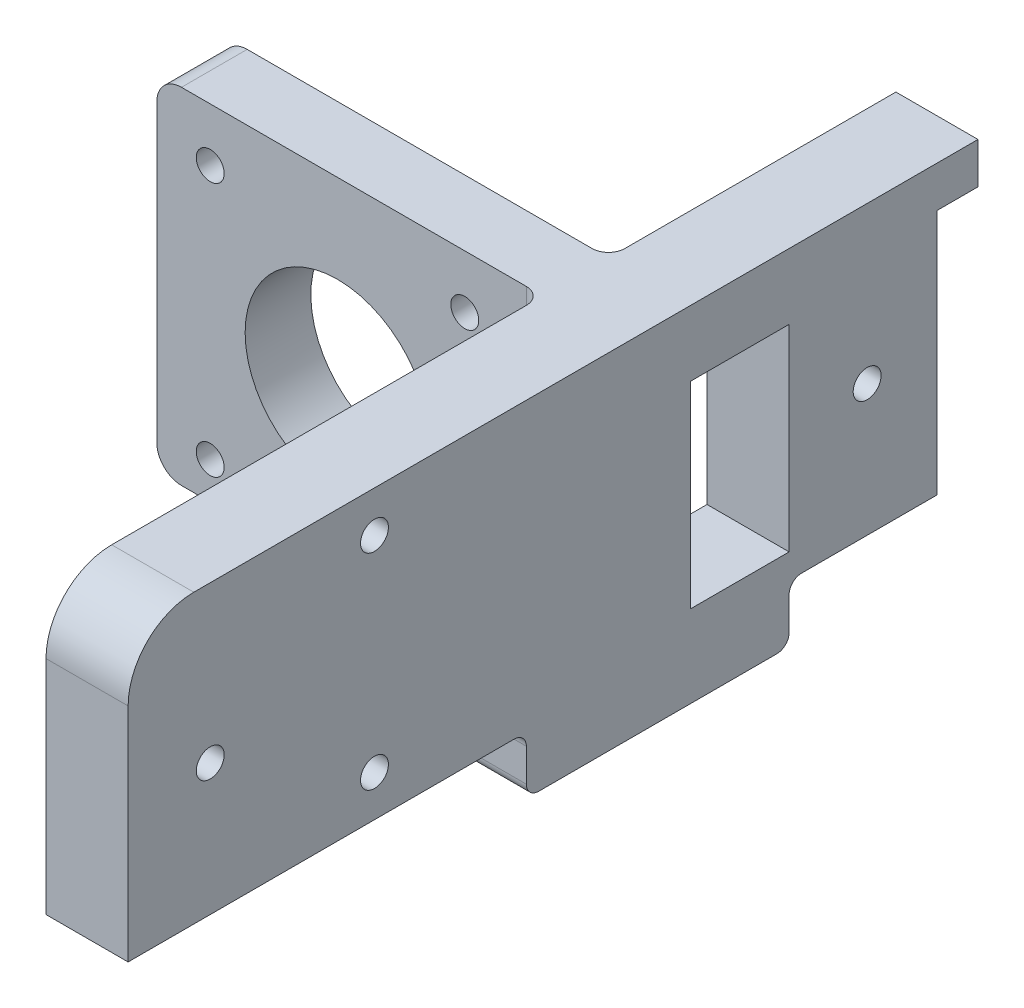
SolidWorks part; units mm, degrees
ref_plane "Front Plane" through (0, 0, 0) normal (0, 0, 1) x (1, 0, 0)
ref_plane "Top Plane" through (0, 0, 0) normal (0, 1, 0) x (1, 0, 0)
ref_plane "Right Plane" through (0, 0, 0) normal (1, 0, 0) x (0, 0, -1)
sketch "Sketch1" plane through (0, 0, 0) normal (1, 0, 0) x (0, 0, -1)
  line L1 (0, 0) -> (-98.5, 0)
  line L2 (0, 0) -> (0, 30)
  line L3 (0, 35) -> (-98.5, 35)
  line L4 (-98.5, 0) -> (-98.5, 35)
  line L5 (0, 35) -> (5, 35)
  line L7 (0, 30) -> (5, 30)
  line L8 (5, 35) -> (5, 30)
  dimension "D1" = 98.5
  dimension "D2" = 35
  dimension "D3" = 5
  dimension "D4" = 5
  dimension "D5" = 5
extrude "Boss-Extrude1" add sketch "Sketch1" along normal blind 10
sketch "Sketch2" plane through (0, 0, 0) normal (-1, 0, 0) x (0, 0, 1)
  line L0 (8.5, 16) -> (88.5, 16) construction
  line L1 (68.5, 30) -> (68.5, 5) construction
  line L2 (0, 0) -> (0, 30) construction
  line L3 (-5, 35) -> (98.5, 35) construction
  dimension "D1" = 80
  dimension "D2" = 8.5
  dimension "D3" = 19
  dimension "D4" = 20
  dimension "D5" = 14
  dimension "D6" = 25
hole_wizard "CSK for M3 Countersunk Flat Head Screw1" positions "3DSketch1" profile "Sketch3" countersink size "M3" standard "DIN" end condition through all
sketch3d "3DSketch1"
  point P0 (0, 16, 8.5)
  point P3 (0, 30, 68.5)
  point P6 (0, 5, 68.5)
  point P9 (0, 16, 88.5)
sketch "Sketch3" plane through (0, 16, 8.5) normal (0, 1, 0) x (0, 0, 1)
  line L0 (0, 0) -> (0, 10)
  line L1 (0, 10) -> (1.7, 10)
  line L2 (1.7, 10) -> (1.7, 1.45)
  line L3 (1.7, 1.45) -> (3.15, 0)
  line L5 (3.15, 0) -> (0, 0)
  line L6 (-1.7, 1.45) -> (-3.15, 0) construction
  line L11 (0, -6.35) -> (0, 107.95) construction
  dimension "Thru Hole Dia." = 3.4
  dimension "Thru Hole Depth" = 10
  dimension "Near C'Sink Dia." = 6.3
  dimension "Near C'Sink Angle" = 90
sketch "Sketch4" plane through (0, 0, 0) normal (-1, 0, 0) x (0, 0, 1)
  line L0 (0, 0) -> (0, 30) construction
  line L1 (18, 3) -> (30, 3)
  line L2 (18, 3) -> (18, 27)
  line L3 (18, 27) -> (30, 27)
  line L4 (30, 3) -> (30, 27)
  line L5 (98.5, 0) -> (0, 0) construction
  dimension "D1" = 12
  dimension "D2" = 24
  dimension "D3" = 18
  dimension "D4" = 3
extrude "Cut-Extrude1" cut sketch "Sketch4" against normal blind 10
sketch "Sketch6" plane through (0, 0, 0) normal (-1, 0, 0) x (0, 0, 1)
  line L0 (98.5, 0) -> (0, 0) construction
  line L3 (18, 0) -> (50, 0)
  line L4 (18, 0) -> (18, -7)
  line L5 (18, -7) -> (50, -7)
  line L6 (50, 0) -> (50, -7)
  line L7 (30, 3) -> (30, 27) construction
  dimension "D1" = 7
  dimension "D2" = 32
  dimension "D3" = 12
extrude "Boss-Extrude3" add sketch "Sketch6" against normal blind 10
sketch "Sketch7" plane through (0, 0, 0) normal (-1, 0, 0) x (0, 0, 1)
  line L0 (-5, 35) -> (98.5, 35) construction
  line L1 (30, 35) -> (38, 35)
  line L2 (30, 35) -> (30, -7)
  line L3 (30, -7) -> (38, -7)
  line L4 (38, 35) -> (38, -7)
  line L5 (18, -7) -> (50, -7) construction
  dimension "D1" = 8
extrude "Boss-Extrude4" add sketch "Sketch7" along normal blind 47
sketch "Sketch8" plane through (0, 0, 30) normal (0, 0, -1) x (-1, 0, 0)
  line L1 (47, 35) -> (47, -7) construction
  line L2 (47, 35) -> (0, 35) construction
  line L3 (40.5, -2.5) -> (9.5, -2.5)
  line L4 (40.5, -2.5) -> (40.5, 28.5)
  line L5 (40.5, 28.5) -> (9.5, 28.5)
  line L6 (9.5, -2.5) -> (9.5, 28.5)
  line L7 (40.5, -2.5) -> (9.5, 28.5) construction
  line L8 (40.5, 28.5) -> (9.5, -2.5) construction
  circle A0 centre (25, 13) radius 11.25
  dimension "D1" = 22
  dimension "D2" = 22
  dimension "D3" = 22.5
  dimension "D4" = 31
  dimension "D5" = 31
extrude "Cut-Extrude2" cut sketch "Sketch8" against normal blind 47 contours A0
hole_wizard "CSK for M3 Countersunk Flat Head Screw2" positions "3DSketch2" profile "Sketch9" countersink size "M3" standard "DIN" end condition through all
sketch3d "3DSketch2"
  point P0 (-9.5, 28.5, 30)
  point P3 (-40.5, 28.5, 30)
  point P6 (-40.5, -2.5, 30)
  point P9 (-9.5, -2.5, 30)
sketch "Sketch9" plane through (-9.5, 28.5, 30) normal (1, 0, 0) x (0, 1, 0)
  line L0 (0, 0) -> (0, 68.5)
  line L1 (0, 68.5) -> (1.7, 68.5)
  line L2 (1.7, 68.5) -> (1.7, 1.45)
  line L3 (1.7, 1.45) -> (3.15, 0)
  line L5 (3.15, 0) -> (0, 0)
  line L6 (-1.7, 1.45) -> (-3.15, 0) construction
  line L11 (0, -6.35) -> (0, 107.95) construction
  dimension "Thru Hole Dia." = 3.4
  dimension "Thru Hole Depth" = 68.5
  dimension "Near C'Sink Dia." = 6.3
  dimension "Near C'Sink Angle" = 90
fillet "Fillet1" radius 8 1 edges at (5, 35, 98.5)
fillet "Fillet2" radius 1.5 4 edges at (5, 0, 50) (5, -7, 50) (5, -7, 18) (5, 0, 18)
fillet "Fillet3" radius 3 2 edges at (-47, -7, 34) (-47, 35, 34)
fillet "Fillet4" radius 2 3 edges at (0, -2, 30) (0, 31, 30) (0, 14, 38)
